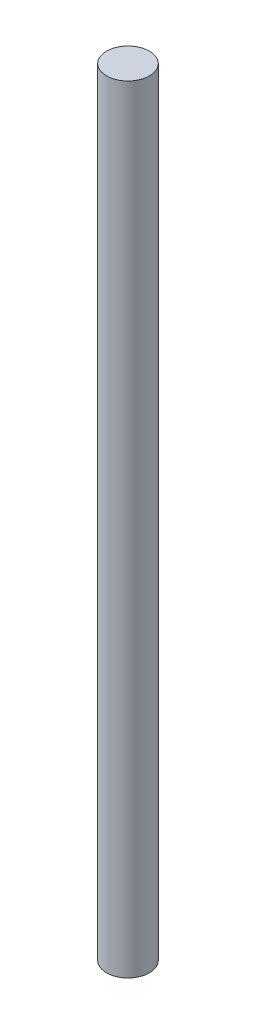
SolidWorks part; units mm, degrees
ref_plane "Front Plane" through (0, 0, 0) normal (0, 0, 1) x (1, 0, 0)
ref_plane "Top Plane" through (0, 0, 0) normal (0, 1, 0) x (1, 0, 0)
ref_plane "Right Plane" through (0, 0, 0) normal (1, 0, 0) x (0, 0, -1)
sketch "Sketch1" plane through (0, 0, 0) normal (0, 1, 0) x (1, 0, 0)
  circle A0 centre (0, 0) radius 1.7526
  dimension "D1" = 3.5052
extrude "Boss-Extrude1" add sketch "Sketch1" along normal blind 63.5
